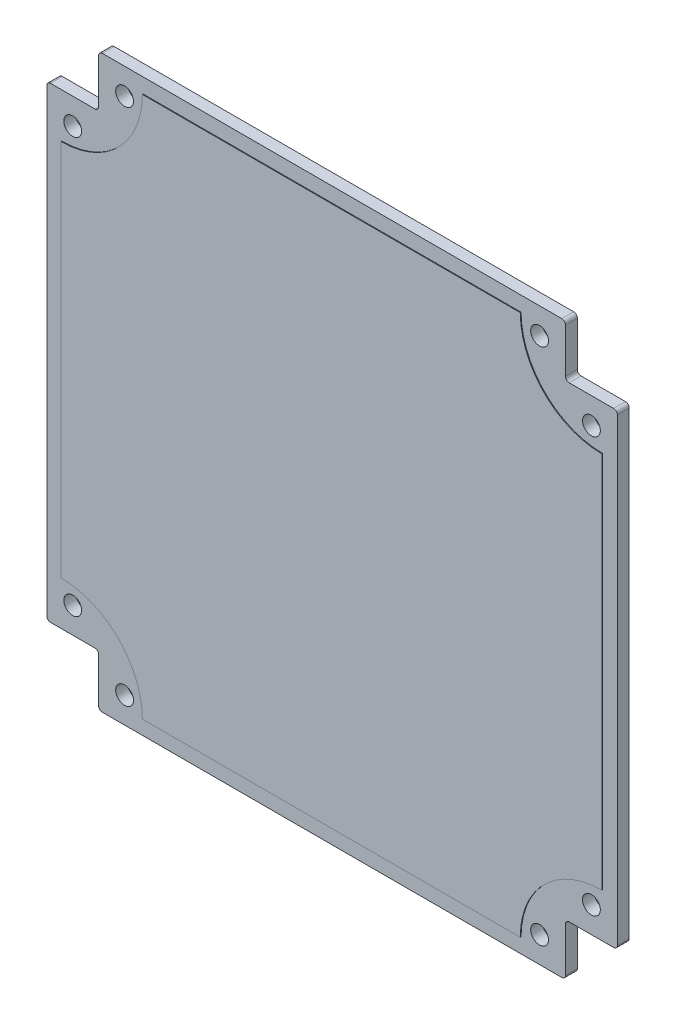
SolidWorks part; units mm, degrees
material "PET"
ref_plane "Front Plane" through (0, 0, 0) normal (0, 0, 1) x (1, 0, 0)
ref_plane "Top Plane" through (0, 0, 0) normal (0, 1, 0) x (1, 0, 0)
ref_plane "Right Plane" through (0, 0, 0) normal (1, 0, 0) x (0, 0, -1)
sketch "Sketch1" plane through (0, 0, 0) normal (0, 0, 1) x (1, 0, 0)
  line L0 (-31.5, 38) -> (-31.5, 32)
  line L1 (-31, -38.5) -> (31, -38.5)
  line L2 (-38.5, 31) -> (-38.5, -31)
  line L3 (-31, 38.5) -> (31, 38.5)
  line L4 (38.5, -31) -> (38.5, 31)
  line L5 (31.5, -38) -> (31.5, -32)
  line L6 (32, -31.5) -> (38, -31.5)
  line L7 (-32, 31.5) -> (-38, 31.5)
  line L8 (31.5, 38) -> (31.5, 32)
  line L9 (32, 31.5) -> (38, 31.5)
  line L10 (-38, -31.5) -> (-32, -31.5)
  line L11 (-31.5, -32) -> (-31.5, -38)
  line L12 (-32, -32) -> (32, 32) construction
  line L13 (32, -32) -> (-32, 32) construction
  arc A0 (-31, 38.5) -> (-31.5, 38) centre (-31, 38) ccw
  arc A1 (31, 38.5) -> (31.5, 38) centre (31, 38) cw
  arc A2 (31.5, 32) -> (32, 31.5) centre (32, 32) ccw
  arc A3 (38, 31.5) -> (38.5, 31) centre (38, 31) cw
  arc A4 (31, -38.5) -> (31.5, -38) centre (31, -38) ccw
  arc A5 (32, -31.5) -> (31.5, -32) centre (32, -32) ccw
  arc A6 (38, -31.5) -> (38.5, -31) centre (38, -31) ccw
  arc A7 (-31.5, -38) -> (-31, -38.5) centre (-31, -38) ccw
  arc A8 (-31.5, -32) -> (-32, -31.5) centre (-32, -32) ccw
  arc A9 (-38.5, -31) -> (-38, -31.5) centre (-38, -31) ccw
  arc A10 (-38, 31.5) -> (-38.5, 31) centre (-38, 31) ccw
  arc A11 (-32, 31.5) -> (-31.5, 32) centre (-32, 32) ccw
  point P0 (0, 0)
  dimension "D4" = 0.5
  dimension "D1" = 7
  dimension "D2" = 7
  dimension "D3" = 7
  dimension "D5" = 7
  dimension "D6" = 7
  dimension "D7" = 7
  dimension "D8" = 7
  dimension "D9" = 7
  dimension "D10" = 77
  dimension "D11" = 77
extrude "Boss-Extrude1" add sketch "Sketch1" along normal blind 1.6
sketch "Esboço1" plane through (0, 0, 1.6) normal (0, 0, 1) x (1, 0, 0)
  line L266 (-38.5, 31) -> (-38.5, -31) construction
  line L267 (31, 38.5) -> (-31, 38.5) construction
  line L268 (38.5, -31) -> (38.5, 31) construction
  line L269 (-31, -38.5) -> (31, -38.5) construction
  line L292 (-25.5, -36.5) -> (25.5, -36.5)
  line L295 (36.5, -25.5) -> (36.5, 25.5)
  line L298 (25.5, 36.5) -> (-25.5, 36.5)
  line L301 (-36.5, 25.5) -> (-36.5, -25.5)
  arc A0 (36.5, -25.5) -> (25.5, -36.5) centre (36.5, -36.5) ccw
  arc A1 (-36.5, -25.5) -> (-25.5, -36.5) centre (-36.5, -36.5) cw
  arc A2 (-25.5, 36.5) -> (-36.5, 25.5) centre (-36.5, 36.5) cw
  arc A3 (25.5, 36.5) -> (36.5, 25.5) centre (36.5, 36.5) ccw
  point P0 (0, 0)
  dimension "D1" = 2
  dimension "D7" = 11
  dimension "D5" = 11
  dimension "D6" = 11
  dimension "D8" = 11
  dimension "D2" = 2
  dimension "D3" = 2
  dimension "D4" = 2
extrude "Boss-Extrude2" add sketch "Esboço1" along normal blind 0.1
hole_wizard "M2 Hole1-FixingStructure" positions "Sketch3" profile "Sketch2" hole size "M2" standard "DIN"
sketch "Sketch3" plane through (0, 0, 0) normal (0, 0, -1) x (-1, 0, 0)
  line L0 (-31, 38.5) -> (31, 38.5) construction
  line L1 (31, -38.5) -> (-31, -38.5) construction
  line L2 (-38.5, -31) -> (-38.5, 31) construction
  line L3 (38.5, 31) -> (38.5, -31) construction
  line L4 (-31, 38.5) -> (31, 38.5) construction
  line L5 (31, -38.5) -> (-31, -38.5) construction
  line L6 (38.5, 31) -> (38.5, -31) construction
  line L7 (-38.5, -31) -> (-38.5, 31) construction
  point P0 (-28, 35)
  point P2 (28, 35)
  point P4 (-28, -35)
  point P6 (28, -35)
  point P20 (35, 28)
  point P22 (35, -28)
  point P24 (-35, -28)
  point P26 (-35, 28)
  dimension "D1" = 3.5
  dimension "D2" = 3.5
  dimension "D3" = 10.5
  dimension "D4" = 10.5
  dimension "D5" = 10.5
  dimension "D6" = 10.5
  dimension "D7" = 3.5
  dimension "D8" = 3.5
sketch "Sketch2" plane through (28, 35, 0) normal (1, 0, 0) x (0, 1, 0)
  line L0 (0, 0) -> (0, 200.721)
  line L1 (0, 200.721) -> (1.2, 200)
  line L2 (1.2, 200) -> (1.2, 0)
  line L5 (1.2, 0) -> (0, 0)
  line L10 (0, 200.721) -> (-1.2, 200) construction
  line L11 (0, -6.35) -> (0, 107.95) construction
  dimension "Hole Dia." = 2.4
  dimension "Hole Depth" = 200
  dimension "Drill Angle" = 118
